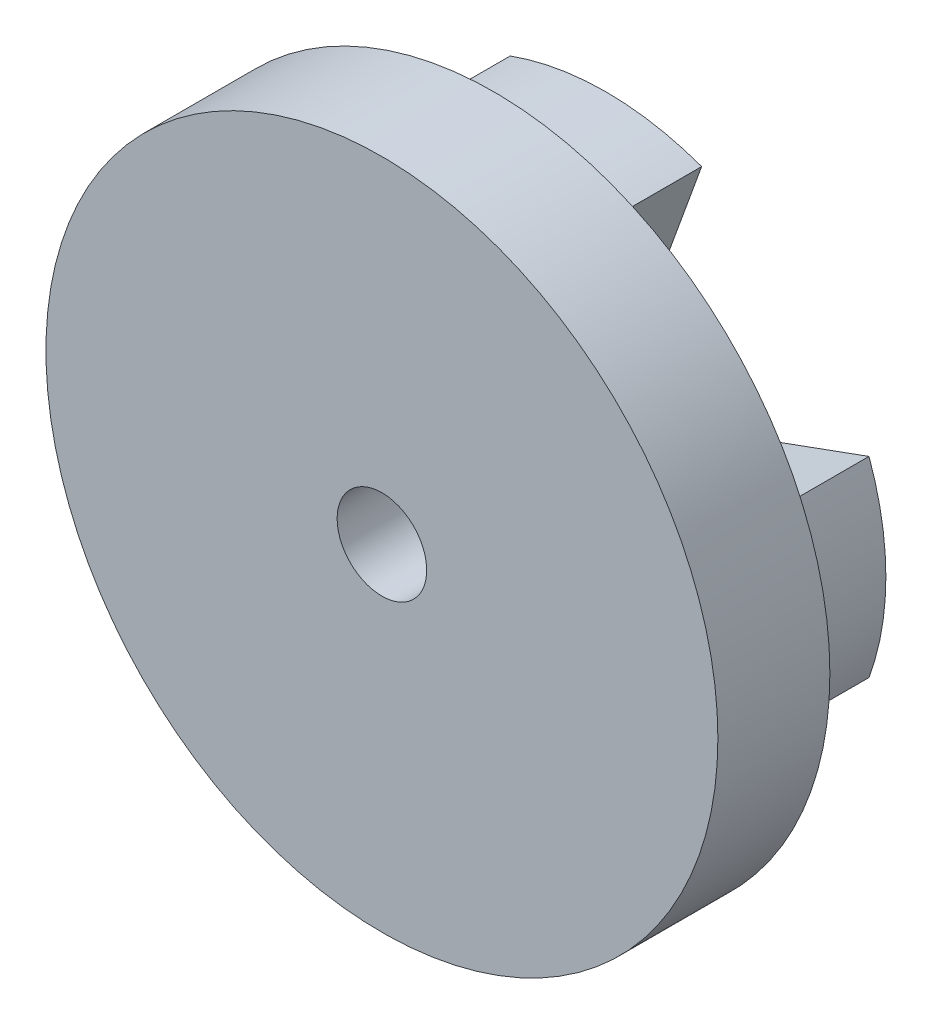
SolidWorks part; units mm, degrees
ref_plane "前视基准面" through (0, 0, 0) normal (0, 0, 1) x (1, 0, 0)
ref_plane "上视基准面" through (0, 0, 0) normal (0, 1, 0) x (1, 0, 0)
ref_plane "右视基准面" through (0, 0, 0) normal (1, 0, 0) x (0, 0, -1)
sketch "草图1" plane through (0, 0, 0) normal (0, 0, 1) x (1, 0, 0)
  circle A0 centre (0, 0) radius 15
  dimension "D1" = 30
extrude "凸台-拉伸1" add sketch "草图1" along normal blind 5
sketch "草图2" plane through (0, 0, 0) normal (0, 0, -1) x (-1, 0, 0)
  line L0 (-2.5652, 7.0477) -> (-4.2753, 11.7462)
  line L1 (0, 7.5) -> (0, 12.5) construction
  line L2 (2.5652, 7.0477) -> (4.2753, 11.7462)
  line L3 (0, 0) -> (-2.5652, 7.0477) construction
  line L4 (0, 0) -> (0, 7.5) construction
  line L5 (0, 0) -> (2.5652, 7.0477) construction
  line L6 (7.0477, 2.5652) -> (11.7462, 4.2753)
  line L7 (7.0477, -2.5652) -> (11.7462, -4.2753)
  line L8 (2.5652, -7.0477) -> (4.2753, -11.7462)
  line L9 (-2.5652, -7.0477) -> (-4.2753, -11.7462)
  line L10 (-7.0477, -2.5652) -> (-11.7462, -4.2753)
  line L11 (-7.0477, 2.5652) -> (-11.7462, 4.2753)
  arc A0 (4.2753, 11.7462) -> (-4.2753, 11.7462) centre (0, 0) ccw
  arc A1 (2.5652, 7.0477) -> (-2.5652, 7.0477) centre (0, 0) ccw
  arc A2 (-4.2753, 11.7462) -> (4.2753, 11.7462) centre (0, 0) ccw construction
  arc A3 (-2.5652, 7.0477) -> (2.5652, 7.0477) centre (0, 0) ccw construction
  arc A4 (11.7462, -4.2753) -> (11.7462, 4.2753) centre (0, 0) ccw
  arc A5 (7.0477, -2.5652) -> (7.0477, 2.5652) centre (0, 0) ccw
  arc A6 (-4.2753, -11.7462) -> (4.2753, -11.7462) centre (0, 0) ccw
  arc A7 (-2.5652, -7.0477) -> (2.5652, -7.0477) centre (0, 0) ccw
  arc A8 (-11.7462, 4.2753) -> (-11.7462, -4.2753) centre (0, 0) ccw
  arc A9 (-7.0477, 2.5652) -> (-7.0477, -2.5652) centre (0, 0) ccw
  point P23 (0, 0)
  dimension "D1" = 25
  dimension "D2" = 15
  dimension "D4" = 40
  dimension "D3" = 4
extrude "凸台-拉伸2" add sketch "草图2" along normal blind 5
sketch "草图3" plane through (0, 0, 0) normal (0, 0, -1) x (-1, 0, 0)
  circle A0 centre (0, 0) radius 2
  dimension "D1" = 4
extrude "切除-拉伸1" cut sketch "草图3" against normal blind 5
